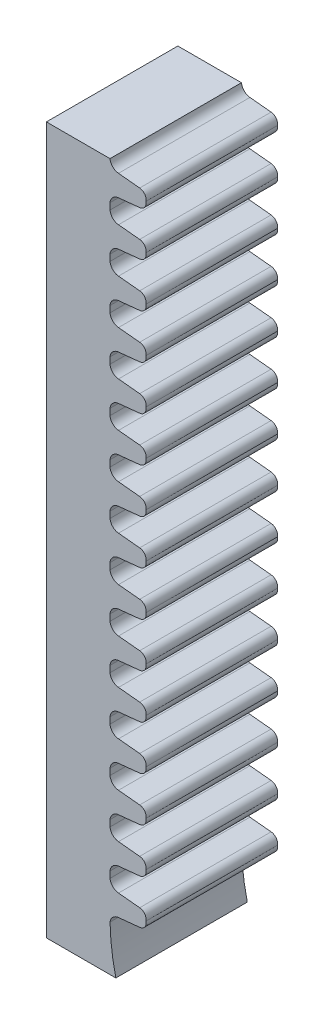
SolidWorks part; units mm, degrees
ref_plane "Front Plane" through (0, 0, 0) normal (0, 0, 1) x (1, 0, 0)
ref_plane "Top Plane" through (0, 0, 0) normal (0, 1, 0) x (1, 0, 0)
ref_plane "Right Plane" through (0, 0, 0) normal (1, 0, 0) x (0, 0, -1)
sketch "Sketch1" plane through (0, 0, 0) normal (0, 0, 1) x (1, 0, 0)
  line L1 (-28, 0) -> (0, 0)
  line L6 (-17.1, 20) -> (-17.1, 51)
  line L7 (-17.1, 51) -> (-20.1, 51)
  line L9 (0, 10) -> (-7.1, 10)
  line L11 (-20.1, 51) -> (-20.1, 6)
  line L12 (-28, 0) -> (-28, 50)
  line L13 (-28, 50) -> (-24, 50)
  line L14 (-24, 50) -> (-24, 6)
  line L15 (-24, 6) -> (-20.1, 6)
  line L16 (0, 10) -> (0, 0)
  arc A1 (-17.1, 20) -> (-7.1, 10) centre (-7.1, 20) ccw
  dimension "D8" = 10
  dimension "D1" = 45
  dimension "D2" = 3.9
  dimension "D3" = 3
  dimension "D4" = 4
  dimension "D5" = 50
  dimension "45" = 28
  dimension "D6" = 6
  dimension "D7" = 10
extrude "Boss-Extrude1" add sketch "Sketch1" along normal blind 6.2
sketch "Sketch2" plane through (0, 0, 0) normal (0, -1, 0) x (1, 0, 0)
  line L0 (0, 6.2) -> (0, 10.4)
  line L1 (0, 10.4) -> (11, 10.4)
  line L2 (11, 10.4) -> (11, 42.4)
  line L3 (11, 42.4) -> (-24.1, 42.4)
  line L4 (-24.1, 42.4) -> (-24.1, 10.4)
  line L5 (-24.1, 10.4) -> (-13.1, 10.4)
  line L6 (-13.1, 10.4) -> (-13.1, 6.2)
  line L7 (-28, 6.2) -> (0, 6.2) construction
  line L8 (-13.1, 6.2) -> (0, 6.2)
  dimension "D1" = 4.2
  dimension "D2" = 7
  dimension "D3" = 11
  dimension "D4" = 11
  dimension "D5" = 32
extrude "Boss-Extrude2" add sketch "Sketch2" against normal blind 21
chamfer "Chamfer1" distance 5 angle 80 1 edges at (-6.55, 0, 42.4)
sketch "Sketch3" plane through (0, 0, 0) normal (1, 0, 0) x (0, 0, -1)
  line L0 (-6.2, 10) -> (-7.6, 10)
  line L1 (-7.6, 10) -> (-10.4, 21)
  line L2 (-10.4, 21) -> (-6.2, 21)
  line L3 (-6.2, 21) -> (-6.2, 10)
  dimension "D1" = 1.4
extrude "Cut-Extrude1" cut sketch "Sketch3" against normal up to next
chamfer "Chamfer2" distance 1 angle 84 1 edges at (11, 10.5, 10.4)
chamfer "Chamfer3" distance 2 angle 45 1 edges at (-24.1, 10.5, 10.4)
sketch "Sketch5" plane through (11, 0, 0) normal (1, 0, 0) x (0, 0, -1)
  line L0 (-42.4, 17.8) -> (-13.8689, 5)
  line L1 (-42.4, 21) -> (-42.4, 5) construction
  line L3 (-13.8689, 5) -> (-10.9662, -4.1087)
  line L4 (-10.9662, -4.1087) -> (-44.0369, 0.9377)
  line L5 (-44.0369, 0.9377) -> (-42.4, 17.8)
  line L6 (-11.4, 21) -> (-10.4, 21) construction
  point P4 (-10.9662, -2.1087)
  point P12 (0, 0)
  point P13 (-11.4, -3.6703)
  point P14 (0, 0)
  dimension "D1" = 3.2
  dimension "D2" = 16
extrude "Cut-Extrude2" cut sketch "Sketch5" against normal up to next
sketch "Sketch6" plane through (0, 0, 10.4) normal (0, 0, -1) x (-1, 0, 0)
  line L0 (13.1, 0) -> (24.1, 5)
  line L1 (24.1, 5) -> (37.1983, 5)
  line L3 (-20.705, 5) -> (-11, 5)
  line L4 (-11, 5) -> (0, 0)
  line L5 (0, 0) -> (13.1, 0)
  line L6 (37.1983, 5) -> (28.626, -4.5222)
  line L7 (28.626, -4.5222) -> (-13.826, -5.6293)
  line L8 (-13.826, -5.6293) -> (-20.705, 5)
extrude "Cut-Extrude3" cut sketch "Sketch6" against normal up to next
sketch "Sketch7" plane through (0, 0, 6.2) normal (0, 0, 1) x (1, 0, 0)
  line L0 (-17.1, 20) -> (-17.1, 51) construction
  line L1 (-15.4, 50.1) -> (-17.4129, 50.1) construction
  line L2 (-16.7, 50.6) -> (-15.7, 50.5)
  line L3 (-16.7, 49.6) -> (-15.7, 49.7)
  line L4 (-17.1, 49.2) -> (-17.1, 48.9)
  line L5 (-17.1, 47.1) -> (-17.1, 46.8)
  line L6 (-16.7, 47.5) -> (-15.7, 47.6)
  line L7 (-16.7, 48.5) -> (-15.7, 48.4)
  line L8 (-17.1, 45) -> (-17.1, 44.7)
  line L9 (-16.7, 45.4) -> (-15.7, 45.5)
  line L10 (-16.7, 46.4) -> (-15.7, 46.3)
  line L11 (-17.1, 42.9) -> (-17.1, 42.6)
  line L12 (-16.7, 43.3) -> (-15.7, 43.4)
  line L13 (-16.7, 44.3) -> (-15.7, 44.2)
  line L14 (-17.1, 40.8) -> (-17.1, 40.5)
  line L15 (-16.7, 41.2) -> (-15.7, 41.3)
  line L16 (-16.7, 42.2) -> (-15.7, 42.1)
  line L17 (-17.1, 38.7) -> (-17.1, 38.4)
  line L18 (-16.7, 39.1) -> (-15.7, 39.2)
  line L19 (-16.7, 40.1) -> (-15.7, 40)
  line L20 (-17.1, 36.6) -> (-17.1, 36.3)
  line L21 (-16.7, 37) -> (-15.7, 37.1)
  line L22 (-16.7, 38) -> (-15.7, 37.9)
  line L23 (-17.1, 34.5) -> (-17.1, 34.2)
  line L24 (-16.7, 34.9) -> (-15.7, 35)
  line L25 (-16.7, 35.9) -> (-15.7, 35.8)
  line L26 (-17.1, 32.4) -> (-17.1, 32.1)
  line L27 (-16.7, 32.8) -> (-15.7, 32.9)
  line L28 (-16.7, 33.8) -> (-15.7, 33.7)
  line L29 (-17.1, 30.3) -> (-17.1, 30)
  line L30 (-16.7, 30.7) -> (-15.7, 30.8)
  line L31 (-16.7, 31.7) -> (-15.7, 31.6)
  line L32 (-17.1, 28.2) -> (-17.1, 27.9)
  line L33 (-16.7, 28.6) -> (-15.7, 28.7)
  line L34 (-16.7, 29.6) -> (-15.7, 29.5)
  line L35 (-17.1, 26.1) -> (-17.1, 25.8)
  line L36 (-16.7, 26.5) -> (-15.7, 26.6)
  line L37 (-16.7, 27.5) -> (-15.7, 27.4)
  line L38 (-17.1, 24) -> (-17.1, 23.7)
  line L39 (-16.7, 24.4) -> (-15.7, 24.5)
  line L40 (-16.7, 25.4) -> (-15.7, 25.3)
  line L41 (-17.1, 21.9) -> (-17.1, 21.6)
  line L42 (-16.7, 22.3) -> (-15.7, 22.4)
  line L43 (-16.7, 23.3) -> (-15.7, 23.2)
  line L44 (-17.1, 19.8) -> (-17.1, 19.5)
  line L45 (-16.7, 20.2) -> (-15.7, 20.3)
  line L46 (-16.7, 21.2) -> (-15.7, 21.1)
  line L47 (-17.1, 19.5) -> (-18.6374, 21.1263)
  line L48 (-18.6374, 21.1263) -> (-18.815, 46.4)
  line L49 (-18.815, 46.4) -> (-17.1, 51)
  arc A0 (-17.1, 51) -> (-16.7, 50.6) centre (-16.6556, 51.0444) ccw
  arc A1 (-15.7, 50.5) -> (-15.4, 50.1) centre (-15.7338, 50.1622) cw
  arc A2 (-17.1, 49.2) -> (-16.7, 49.6) centre (-16.6556, 49.1556) cw
  arc A3 (-15.7, 49.7) -> (-15.4, 50.1) centre (-15.7338, 50.0378) ccw
  arc A4 (-17.1, 47.1) -> (-16.7, 47.5) centre (-16.6556, 47.0556) cw
  arc A5 (-15.7, 47.6) -> (-15.4, 48) centre (-15.7338, 47.9378) ccw
  arc A6 (-15.7, 48.4) -> (-15.4, 48) centre (-15.7338, 48.0622) cw
  arc A7 (-17.1, 48.9) -> (-16.7, 48.5) centre (-16.6556, 48.9444) ccw
  arc A8 (-17.1, 45) -> (-16.7, 45.4) centre (-16.6556, 44.9556) cw
  arc A9 (-15.7, 45.5) -> (-15.4, 45.9) centre (-15.7338, 45.8378) ccw
  arc A10 (-15.7, 46.3) -> (-15.4, 45.9) centre (-15.7338, 45.9622) cw
  arc A11 (-17.1, 46.8) -> (-16.7, 46.4) centre (-16.6556, 46.8444) ccw
  arc A12 (-17.1, 42.9) -> (-16.7, 43.3) centre (-16.6556, 42.8556) cw
  arc A13 (-15.7, 43.4) -> (-15.4, 43.8) centre (-15.7338, 43.7378) ccw
  arc A14 (-15.7, 44.2) -> (-15.4, 43.8) centre (-15.7338, 43.8622) cw
  arc A15 (-17.1, 44.7) -> (-16.7, 44.3) centre (-16.6556, 44.7444) ccw
  arc A16 (-17.1, 40.8) -> (-16.7, 41.2) centre (-16.6556, 40.7556) cw
  arc A17 (-15.7, 41.3) -> (-15.4, 41.7) centre (-15.7338, 41.6378) ccw
  arc A18 (-15.7, 42.1) -> (-15.4, 41.7) centre (-15.7338, 41.7622) cw
  arc A19 (-17.1, 42.6) -> (-16.7, 42.2) centre (-16.6556, 42.6444) ccw
  arc A20 (-17.1, 38.7) -> (-16.7, 39.1) centre (-16.6556, 38.6556) cw
  arc A21 (-15.7, 39.2) -> (-15.4, 39.6) centre (-15.7338, 39.5378) ccw
  arc A22 (-15.7, 40) -> (-15.4, 39.6) centre (-15.7338, 39.6622) cw
  arc A23 (-17.1, 40.5) -> (-16.7, 40.1) centre (-16.6556, 40.5444) ccw
  arc A24 (-17.1, 36.6) -> (-16.7, 37) centre (-16.6556, 36.5556) cw
  arc A25 (-15.7, 37.1) -> (-15.4, 37.5) centre (-15.7338, 37.4378) ccw
  arc A26 (-15.7, 37.9) -> (-15.4, 37.5) centre (-15.7338, 37.5622) cw
  arc A27 (-17.1, 38.4) -> (-16.7, 38) centre (-16.6556, 38.4444) ccw
  arc A28 (-17.1, 34.5) -> (-16.7, 34.9) centre (-16.6556, 34.4556) cw
  arc A29 (-15.7, 35) -> (-15.4, 35.4) centre (-15.7338, 35.3378) ccw
  arc A30 (-15.7, 35.8) -> (-15.4, 35.4) centre (-15.7338, 35.4622) cw
  arc A31 (-17.1, 36.3) -> (-16.7, 35.9) centre (-16.6556, 36.3444) ccw
  arc A32 (-17.1, 32.4) -> (-16.7, 32.8) centre (-16.6556, 32.3556) cw
  arc A33 (-15.7, 32.9) -> (-15.4, 33.3) centre (-15.7338, 33.2378) ccw
  arc A34 (-15.7, 33.7) -> (-15.4, 33.3) centre (-15.7338, 33.3622) cw
  arc A35 (-17.1, 34.2) -> (-16.7, 33.8) centre (-16.6556, 34.2444) ccw
  arc A36 (-17.1, 30.3) -> (-16.7, 30.7) centre (-16.6556, 30.2556) cw
  arc A37 (-15.7, 30.8) -> (-15.4, 31.2) centre (-15.7338, 31.1378) ccw
  arc A38 (-15.7, 31.6) -> (-15.4, 31.2) centre (-15.7338, 31.2622) cw
  arc A39 (-17.1, 32.1) -> (-16.7, 31.7) centre (-16.6556, 32.1444) ccw
  arc A40 (-17.1, 28.2) -> (-16.7, 28.6) centre (-16.6556, 28.1556) cw
  arc A41 (-15.7, 28.7) -> (-15.4, 29.1) centre (-15.7338, 29.0378) ccw
  arc A42 (-15.7, 29.5) -> (-15.4, 29.1) centre (-15.7338, 29.1622) cw
  arc A43 (-17.1, 30) -> (-16.7, 29.6) centre (-16.6556, 30.0444) ccw
  arc A44 (-17.1, 26.1) -> (-16.7, 26.5) centre (-16.6556, 26.0556) cw
  arc A45 (-15.7, 26.6) -> (-15.4, 27) centre (-15.7338, 26.9378) ccw
  arc A46 (-15.7, 27.4) -> (-15.4, 27) centre (-15.7338, 27.0622) cw
  arc A47 (-17.1, 27.9) -> (-16.7, 27.5) centre (-16.6556, 27.9444) ccw
  arc A48 (-17.1, 24) -> (-16.7, 24.4) centre (-16.6556, 23.9556) cw
  arc A49 (-15.7, 24.5) -> (-15.4, 24.9) centre (-15.7338, 24.8378) ccw
  arc A50 (-15.7, 25.3) -> (-15.4, 24.9) centre (-15.7338, 24.9622) cw
  arc A51 (-17.1, 25.8) -> (-16.7, 25.4) centre (-16.6556, 25.8444) ccw
  arc A52 (-17.1, 21.9) -> (-16.7, 22.3) centre (-16.6556, 21.8556) cw
  arc A53 (-15.7, 22.4) -> (-15.4, 22.8) centre (-15.7338, 22.7378) ccw
  arc A54 (-15.7, 23.2) -> (-15.4, 22.8) centre (-15.7338, 22.8622) cw
  arc A55 (-17.1, 23.7) -> (-16.7, 23.3) centre (-16.6556, 23.7444) ccw
  arc A56 (-17.1, 19.8) -> (-16.7, 20.2) centre (-16.6556, 19.7556) cw
  arc A57 (-15.7, 20.3) -> (-15.4, 20.7) centre (-15.7338, 20.6378) ccw
  arc A58 (-15.7, 21.1) -> (-15.4, 20.7) centre (-15.7338, 20.7622) cw
  arc A59 (-17.1, 21.6) -> (-16.7, 21.2) centre (-16.6556, 21.6444) ccw
  point P186 (-17.1, 48.8834)
  dimension "D1" = 0.4
  dimension "D6" = 0.4
  dimension "D2" = 0.3
  dimension "D3" = 0.4
  dimension "D4" = 0.1
  dimension "D5" = 1
  dimension "D7" = 15
extrude "Boss-Extrude3" add sketch "Sketch7" against normal up to surface (6.2 mm away) up to face at (-17.0519, 22.9026, 0)
sketch "Sketch8" plane through (11, 0, 0) normal (1, 0, 0) x (0, 0, -1)
  line L0 (-35.4, 21) -> (-27.4, 17)
  line L1 (-11.4, 21) -> (-42.4, 21) construction
  line L2 (-27.4, 17) -> (-19.4, 21)
  line L3 (-19.4, 21) -> (-35.4, 21)
  dimension "D1" = 4
  dimension "D2" = 16
  dimension "D3" = 7
  dimension "D4" = 8
extrude "Cut-Extrude4" cut sketch "Sketch8" against normal up to next
sketch "Sketch9" plane through (0, 0, 6.2) normal (0, 0, 1) x (1, 0, 0)
  line L1 (-29.231, 51.7369) -> (-20.8042, 51.7369)
  line L2 (-29.231, 51.7369) -> (-29.231, -2.081)
  line L3 (-29.231, -2.081) -> (-20.8042, -2.081)
  line L4 (-20.8042, 51.7369) -> (-20.8042, -2.081)
extrude "Cut-Extrude5" cut sketch "Sketch9" against normal through all both and the other way through all
sketch "Sketch10" plane through (0, 0, 6.2) normal (0, 0, 1) x (1, 0, 0)
  line L1 (-29.7173, 17.6677) -> (11.538, 17.6677)
  line L2 (-29.7173, 17.6677) -> (-29.7173, -1.4607)
  line L3 (-29.7173, -1.4607) -> (11.538, -1.4607)
  line L4 (11.538, 17.6677) -> (11.538, -1.4607)
extrude "Cut-Extrude6" cut sketch "Sketch10" against normal through all both and the other way through all
sketch "Sketch11" plane through (0, 0, 6.2) normal (0, 0, 1) x (1, 0, 0)
  line L1 (-22.5312, 21.4417) -> (14.278, 21.4417)
  line L2 (-22.5312, 21.4417) -> (-22.5312, 15.6515)
  line L3 (-22.5312, 15.6515) -> (14.278, 15.6515)
  line L4 (14.278, 21.4417) -> (14.278, 15.6515)
extrude "Cut-Extrude7" cut sketch "Sketch11" along normal through all
equation "\"D4@Sketch8\"=\"D2@Sketch8\"/2"
